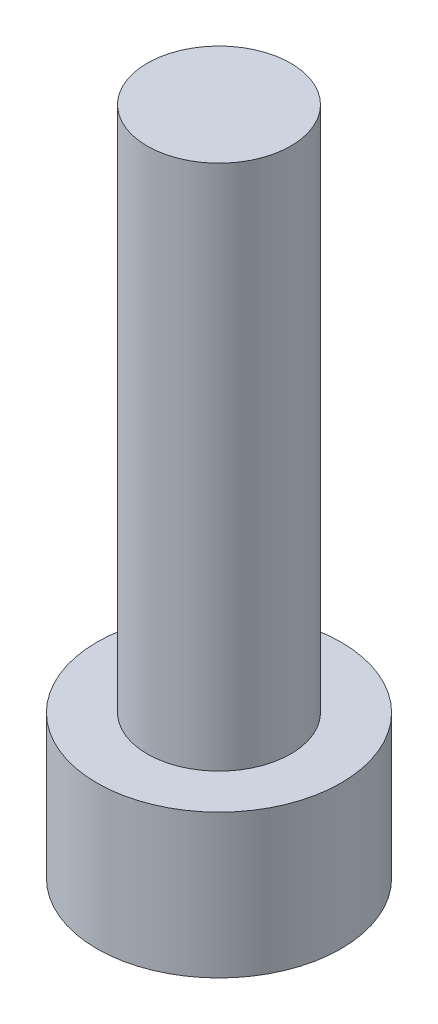
SolidWorks part; units mm, degrees
ref_plane "前视基准面" through (0, 0, 0) normal (0, 0, 1) x (1, 0, 0)
ref_plane "上视基准面" through (0, 0, 0) normal (0, 1, 0) x (1, 0, 0)
ref_plane "右视基准面" through (0, 0, 0) normal (1, 0, 0) x (0, 0, -1)
other "Configuration Table"
sketch "草图1" plane through (0, 0, 0) normal (0, 1, 0) x (1, 0, 0)
  circle A0 centre (0, 0) radius 5.1
  dimension "D1" = 10.2
extrude "凸台-拉伸1" add sketch "草图1" along normal blind 6
sketch "草图2" plane through (0, 6, 0) normal (0, 1, 0) x (1, 0, 0)
  circle A0 centre (0, 0) radius 3
  dimension "D1" = 6
extrude "凸台-拉伸2" add sketch "草图2" along normal blind 22
cosmetic thread "装饰螺纹线1" parameters "D2"=5
sketch "草图3" plane through (0, 0, 0) normal (0, -1, 0) x (1, 0, 0)
  line L1 (2.3571, -1.6665) -> (2.6218, 1.2081)
  line L2 (2.6218, 1.2081) -> (0.2647, 2.8746)
  line L3 (0.2647, 2.8746) -> (-2.3571, 1.6665)
  line L4 (-2.3571, 1.6665) -> (-2.6218, -1.2081)
  line L5 (-2.6218, -1.2081) -> (-0.2647, -2.8746)
  line L6 (-0.2647, -2.8746) -> (2.3571, -1.6665)
  circle A0 centre (0, 0) radius 2.5 construction
  dimension "D1" = 5
extrude "切除-拉伸1" cut sketch "草图3" against normal blind 3
